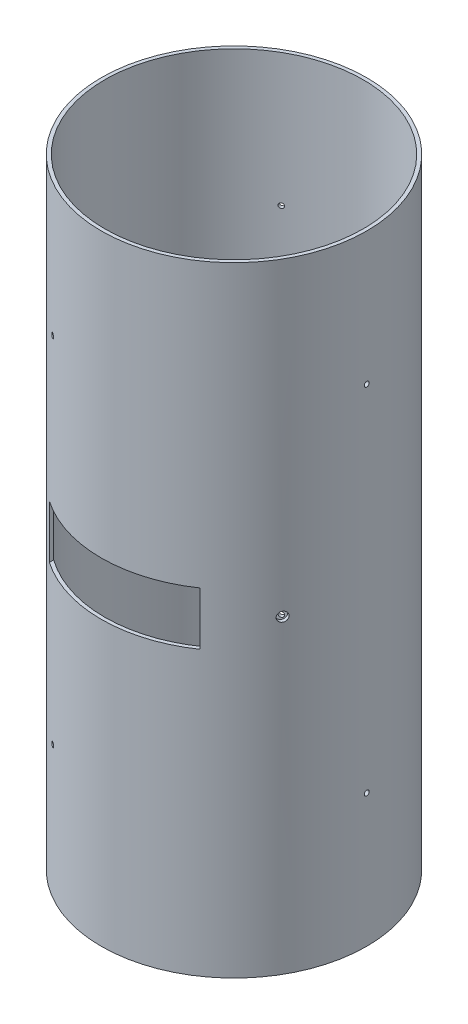
SolidWorks part; units mm, degrees
ref_plane "Front Plane" through (0, 0, 0) normal (0, 0, 1) x (1, 0, 0)
ref_plane "Top Plane" through (0, 0, 0) normal (0, 1, 0) x (1, 0, 0)
ref_plane "Right Plane" through (0, 0, 0) normal (1, 0, 0) x (0, 0, -1)
sketch "Sketch1" plane through (0, 0, 0) normal (0, 1, 0) x (1, 0, 0)
  circle A0 centre (0, 0) radius 74.168
  circle A1 centre (0, 0) radius 76.2
  dimension "D1" = 148.336
  dimension "D2" = 152.4
extrude "Boss-Extrude1" add sketch "Sketch1" along normal blind 355.6
sketch "Sketch2" plane through (0, 0, 0) normal (0, 0, 1) x (1, 0, 0)
  line L0 (0, -83.82) -> (0, 83.82) construction
  line L1 (-43.18, 193.04) -> (43.18, 193.04)
  line L2 (-43.18, 193.04) -> (-43.18, 162.56)
  line L3 (-43.18, 162.56) -> (43.18, 162.56)
  line L4 (43.18, 193.04) -> (43.18, 162.56)
  line L5 (-43.18, 193.04) -> (43.18, 162.56) construction
  line L6 (-43.18, 162.56) -> (43.18, 193.04) construction
  line L7 (83.82, 0) -> (-83.82, 0) construction
  point P0 (0, 177.8)
  dimension "D1" = 86.36
  dimension "D2" = 30.48
  dimension "D3" = 177.8
extrude "Cut-Extrude1" cut sketch "Sketch2" along normal blind 90.424
ref_plane "Plane1" through (-65.9911, 0, 38.1) normal (-0.866, 0, 0.5) x (0, -1, 0)
sketch "Sketch3" plane through (-65.9911, 0, 38.1) normal (-0.866, 0, 0.5) x (0, -1, 0)
  line L0 (-193.04, 30.6334) -> (-193.04, 74.168) construction
  circle A0 centre (-177.8, 0) radius 2.7305
  dimension "D1" = 5.461
  dimension "D2" = 15.24
extrude "Cut-Extrude2" cut sketch "Sketch3" against normal blind 2.54
pattern_circular "CirPattern1" count 4 every 80 about axis through (0, 355.6, 0) along (0, -1, 0) of "Cut-Extrude2"
sketch "Sketch4" plane through (0, 0, 20.4177) normal (-1, 0, 0) x (0, -1, 0)
  circle A0 centre (-76.2, -20.4177) radius 1.4122
  circle A1 centre (-279.4, -20.4177) radius 1.4122
  point P4 (0, 0)
  dimension "D1" = 2.8245
  dimension "D2" = 76.2
  dimension "D3" = 203.2
extrude "Cut-Extrude3" cut sketch "Sketch4" against normal up to surface (76.1869 mm away)
pattern_circular "CirPattern2" count 3 over 360 about axis through (0, 355.6, 0) along (0, 1, 0) of "Cut-Extrude3"
